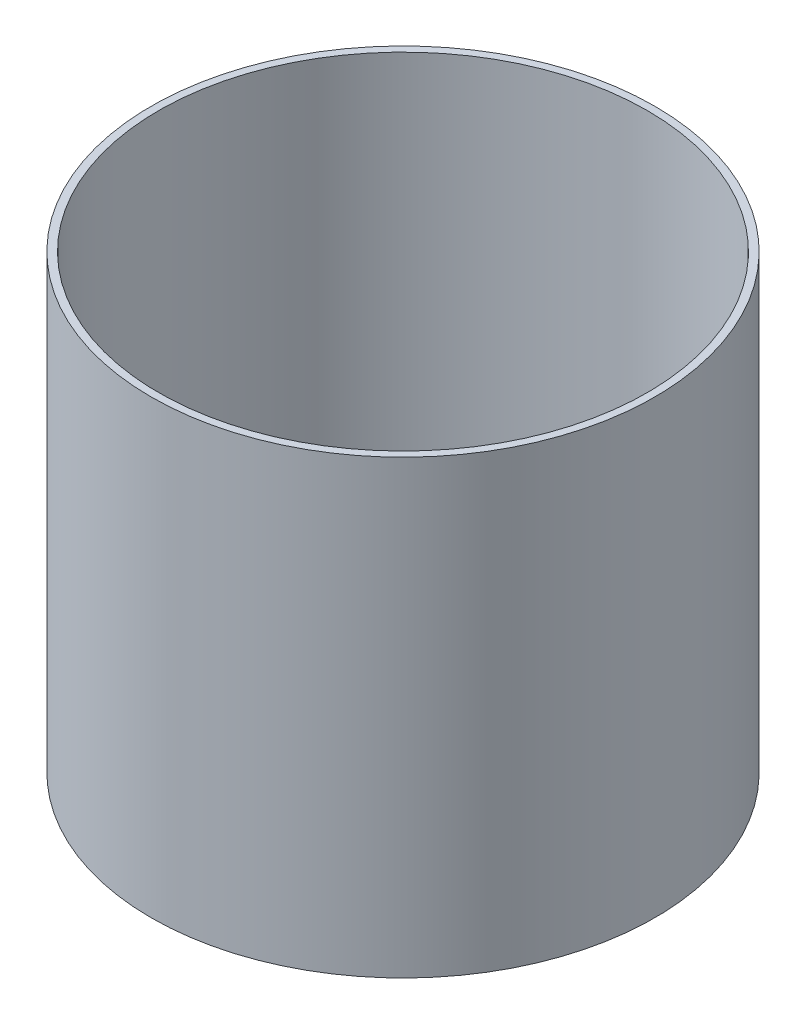
SolidWorks part; units mm, degrees
ref_plane "Front Plane" through (0, 0, 0) normal (0, 0, 1) x (1, 0, 0)
ref_plane "Top Plane" through (0, 0, 0) normal (0, 1, 0) x (1, 0, 0)
ref_plane "Right Plane" through (0, 0, 0) normal (1, 0, 0) x (0, 0, -1)
sketch "Sketch1" plane through (0, 0, 0) normal (0, 1, 0) x (1, 0, 0)
  circle A0 centre (0, 0) radius 82.55
  circle A1 centre (0, 0) radius 85.09
  dimension "D1" = 170.18
  dimension "D2" = 165.1
extrude "Boss-Extrude1" add sketch "Sketch1" along normal blind 152.4
